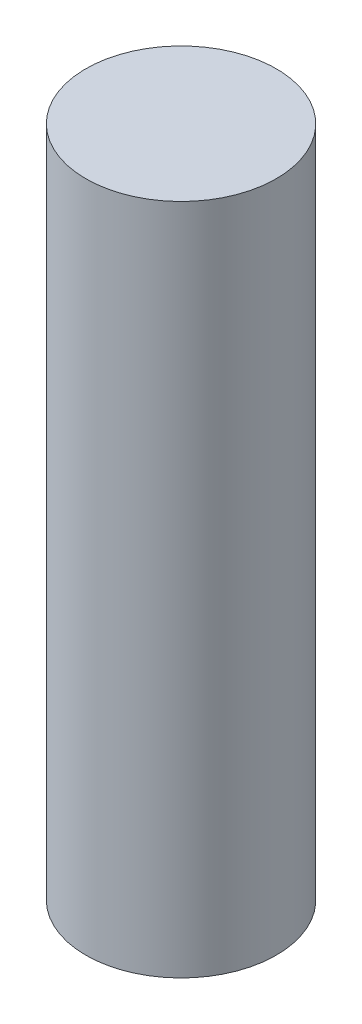
SolidWorks part; units mm, degrees
ref_plane "Front Plane" through (0, 0, 0) normal (0, 0, 1) x (1, 0, 0)
ref_plane "Top Plane" through (0, 0, 0) normal (0, 1, 0) x (1, 0, 0)
ref_plane "Right Plane" through (0, 0, 0) normal (1, 0, 0) x (0, 0, -1)
sketch "Sketch3" plane through (0, 0, 0) normal (0, 1, 0) x (1, 0, 0)
  circle A0 centre (0, 0) radius 0.85
  dimension "D1" = 1.7
extrude "Boss-Extrude1" add sketch "Sketch3" along normal blind 6
